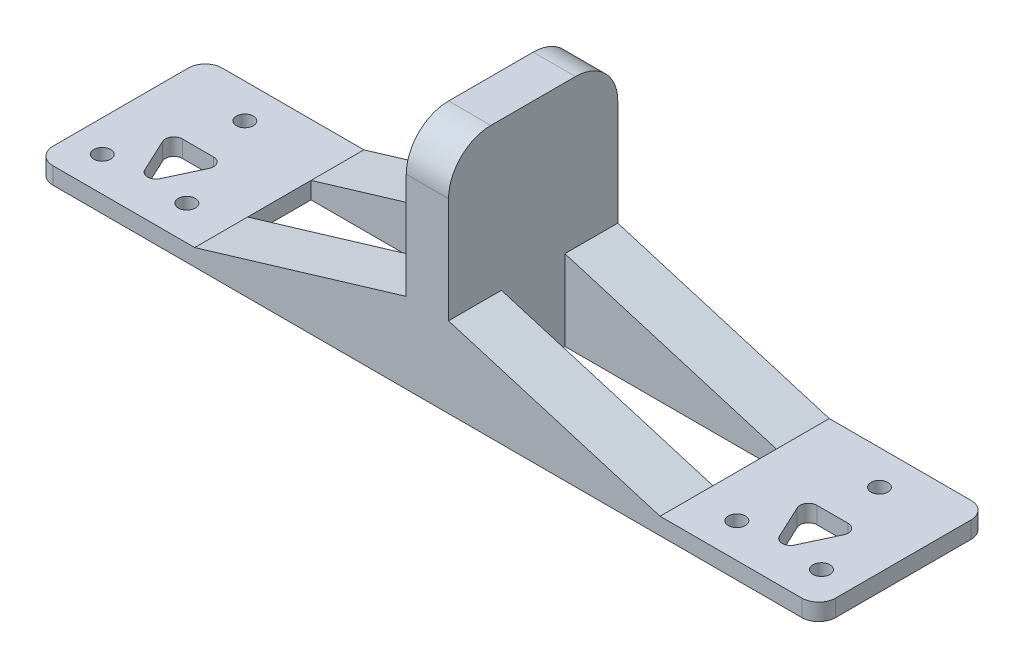
SolidWorks part; units mm, degrees
ref_plane "前视基准面" through (0, 0, 0) normal (0, 0, 1) x (1, 0, 0)
ref_plane "上视基准面" through (0, 0, 0) normal (0, 1, 0) x (1, 0, 0)
ref_plane "右视基准面" through (0, 0, 0) normal (1, 0, 0) x (0, 0, -1)
other "Configuration Table"
sketch "草图1" plane through (0, 0, 0) normal (0, 1, 0) x (1, 0, 0)
  line L1 (-92.5, 20) -> (92.5, 20)
  line L2 (-92.5, 20) -> (-92.5, -20)
  line L3 (-92.5, -20) -> (92.5, -20)
  line L4 (92.5, 20) -> (92.5, -20)
  line L5 (-92.5, 20) -> (92.5, -20) construction
  line L6 (-92.5, -20) -> (92.5, 20) construction
  point P0 (0, 0)
  dimension "D1" = 185
  dimension "D2" = 40
extrude "凸台-拉伸1" add sketch "草图1" against normal blind 4
sketch "草图2" plane through (0, 0, 0) normal (0, 1, 0) x (1, 0, 0)
  line L0 (0, 20) -> (0, -20) construction
  line L1 (92.5, 20) -> (-92.5, 20) construction
  line L2 (-92.5, -20) -> (92.5, -20) construction
  line L3 (-75, 20) -> (-75, -20) construction
  line L4 (-75, 0) -> (0, 0) construction
  line L5 (-75, -11.85) -> (-75, 11.85) construction
  line L6 (-75, -11.85) -> (-65, -11.85) construction
  circle A0 centre (-75, 11.85) radius 2
  circle A1 centre (-65, -11.85) radius 2
  circle A2 centre (-85, -11.85) radius 2
  circle A3 centre (65, -11.85) radius 2
  circle A4 centre (85, -11.85) radius 2
  circle A5 centre (75, 11.85) radius 2
  point P13 (-75, 0)
  dimension "D3" = 4
  dimension "D5" = 4
  dimension "D1" = 75
  dimension "D2" = 23.7
  dimension "D4" = 10
extrude "切除-拉伸1" cut sketch "草图2" against normal through all both and the other way through all
sketch "草图3" plane through (0, 0, 0) normal (0, 1, 0) x (1, 0, 0)
  line L0 (-92.5, -20) -> (92.5, -20) construction
  line L1 (-5, 20) -> (5, 20)
  line L2 (-5, 20) -> (-5, -20)
  line L3 (-5, -20) -> (5, -20)
  line L4 (5, 20) -> (5, -20)
  line L5 (-5, 20) -> (5, -20) construction
  line L6 (-5, -20) -> (5, 20) construction
  point P0 (0, 0)
  dimension "D1" = 10
extrude "凸台-拉伸2" add sketch "草图3" along normal blind 50
sketch "草图4" plane through (0, 0, 0) normal (0, 0, 1) x (1, 0, 0)
  line L0 (-5, 0) -> (-5, 15)
  line L1 (-5, 50) -> (-5, 0) construction
  line L2 (-5, 15) -> (-55, 0)
  line L3 (-92.5, 0) -> (-5, 0) construction
  line L4 (-55, 0) -> (-5, 0)
  line L5 (0, -4) -> (0, 50) construction
  line L6 (-92.5, -4) -> (92.5, -4) construction
  line L7 (-5, 50) -> (5, 50) construction
  line L8 (5, 15) -> (55, 0)
  line L9 (5, 0) -> (5, 15)
  line L10 (55, 0) -> (5, 0)
  dimension "D1" = 15
  dimension "D2" = 50
extrude "凸台-拉伸3" add sketch "草图4" along normal mid plane 40
sketch "草图5" plane through (0, 0, 0) normal (0, 1, 0) x (1, 0, 0)
  line L0 (-92.5, 0) -> (92.5, 0) construction
  line L1 (-92.5, 20) -> (-92.5, -20) construction
  line L2 (92.5, -20) -> (92.5, 20) construction
  line L3 (0, 20) -> (0, -20) construction
  line L4 (5, 20) -> (-5, 20) construction
  line L5 (-5, -20) -> (5, -20) construction
  line L16 (-5, -20) -> (-5, 20) construction
  line L17 (-5, 7.5) -> (-55, 7.5)
  line L19 (-5, 7.5) -> (-5, -7.5)
  line L20 (-5, -7.5) -> (-55, -7.5)
  line L21 (-55, 7.5) -> (-55, -7.5)
  line L22 (-55, -20) -> (-55, 20) construction
  line L27 (-73.1573, 12.6275) -> (-63.1573, -11.0725) construction
  line L28 (-85, -13.85) -> (-65, -13.85) construction
  line L29 (-81.8427, 0.7775) -> (-75, -13.85)
  line L30 (-86.8427, -11.0725) -> (-76.8427, 12.6275) construction
  line L31 (-75, -13.85) -> (-68.1573, 0.7775)
  line L32 (-68.1573, 0.7775) -> (-81.8427, 0.7775)
  line L33 (75, -13.85) -> (68.1573, 0.7775)
  line L34 (81.8427, 0.7775) -> (75, -13.85)
  line L35 (68.1573, 0.7775) -> (81.8427, 0.7775)
  line L36 (5, -7.5) -> (55, -7.5)
  line L37 (55, 7.5) -> (55, -7.5)
  line L38 (5, 7.5) -> (55, 7.5)
  line L39 (5, 7.5) -> (5, -7.5)
  circle A0 centre (-85, -11.85) radius 2 construction
  circle A1 centre (-75, 11.85) radius 2 construction
  circle A2 centre (-65, -11.85) radius 2 construction
  point P20 (-5, 0)
  dimension "D1" = 15
extrude "切除-拉伸2" cut sketch "草图5" against normal through all both and the other way through all
fillet "圆角1" radius 10 2 edges at (0, 50, 20) (0, 50, -20)
fillet "圆角2" radius 4 4 edges at (92.5, -2, 20) (92.5, -2, -20) (-92.5, -2, 20) (-92.5, -2, -20)
fillet "圆角3" radius 2 6 edges at (81.8427, -2, -0.7775) (75, -2, 13.85) (68.1573, -2, -0.7775) (-68.1573, -2, -0.7775) (-75, -2, 13.85) (-81.8427, -2, -0.7775)
